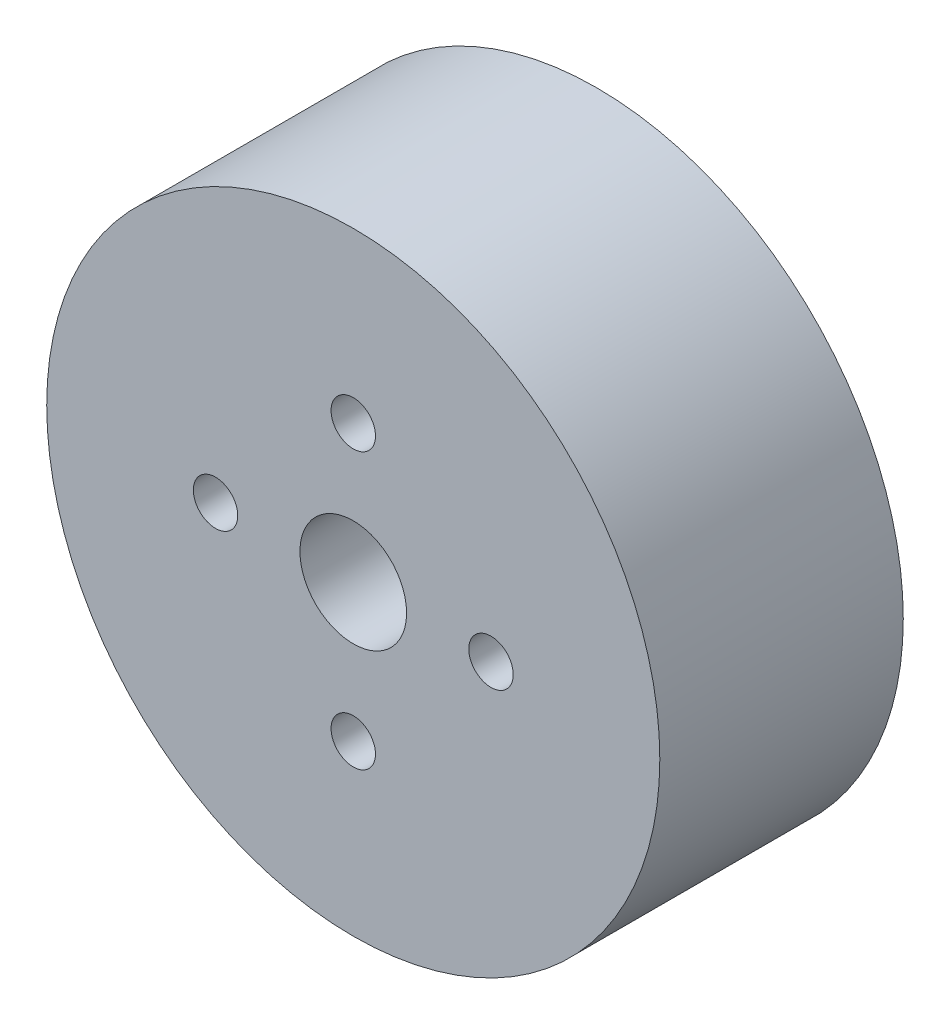
SolidWorks part; units mm, degrees
ref_plane "前视基准面" through (0, 0, 0) normal (0, 0, 1) x (1, 0, 0)
ref_plane "上视基准面" through (0, 0, 0) normal (0, 1, 0) x (1, 0, 0)
ref_plane "右视基准面" through (0, 0, 0) normal (1, 0, 0) x (0, 0, -1)
sketch "草图1" plane through (0, 0, 0) normal (0, 0, 1) x (1, 0, 0)
  circle A0 centre (0, 0) radius 17.25
  dimension "D1" = 34.5
extrude "凸台-拉伸1" add sketch "草图1" along normal blind 13.7
ref_plane "基准面1" through (0, 0, 13.7) normal (0, 0, 1) x (1, 0, 0)
sketch "草图2" plane through (0, 0, 13.7) normal (0, 0, 1) x (1, 0, 0)
  circle A0 centre (0, 0) radius 7.75 construction
  circle A1 centre (0, 7.75) radius 1.25
  circle A2 centre (7.75, 0) radius 1.25
  circle A3 centre (0, -7.75) radius 1.25
  circle A4 centre (-7.75, 0) radius 1.25
  dimension "D1" = 2.5
  dimension "D2" = 15.5
  dimension "D3" = 4
extrude "切除-拉伸1" cut sketch "草图2" against normal blind 3
sketch "草图3" plane through (0, 0, 0) normal (0, 0, 1) x (1, 0, 0)
  circle A0 centre (0, 0) radius 7.75 construction
  circle A1 centre (0, 7.75) radius 1.25
  circle A2 centre (7.75, 0) radius 1.25
  circle A3 centre (0, -7.75) radius 1.25
  circle A4 centre (-7.75, 0) radius 1.25
  dimension "D1" = 15.5
  dimension "D3" = 2.5
  dimension "D2" = 4
extrude "切除-拉伸2" cut sketch "草图3" along normal blind 3
sketch "草图4" plane through (0, 0, 0) normal (0, 0, 1) x (1, 0, 0)
  circle A0 centre (0, 0) radius 4.25
  circle A1 centre (0, 0) radius 6.25
  dimension "D1" = 2
  dimension "D2" = 12.5
extrude "切除-拉伸3" cut sketch "草图4" along normal blind 2
sketch "草图5" plane through (0, 0, 0) normal (0, 0, 1) x (1, 0, 0)
  circle A0 centre (0, 0) radius 3.25
  circle A1 centre (0, 0) radius 4.25 construction
  dimension "D1" = 1
extrude "切除-拉伸4" cut sketch "草图5" along normal blind 0.7
fillet "圆角1" radius 0.3 2 edges at (3.25, 0, 0) (4.25, 0, 0)
sketch "草图6" plane through (0, 0, 13.7) normal (0, 0, 1) x (1, 0, 0)
  circle A0 centre (0, 0) radius 3
  dimension "D1" = 6
extrude "切除-拉伸6" cut sketch "草图6" against normal blind 11 contours A0
